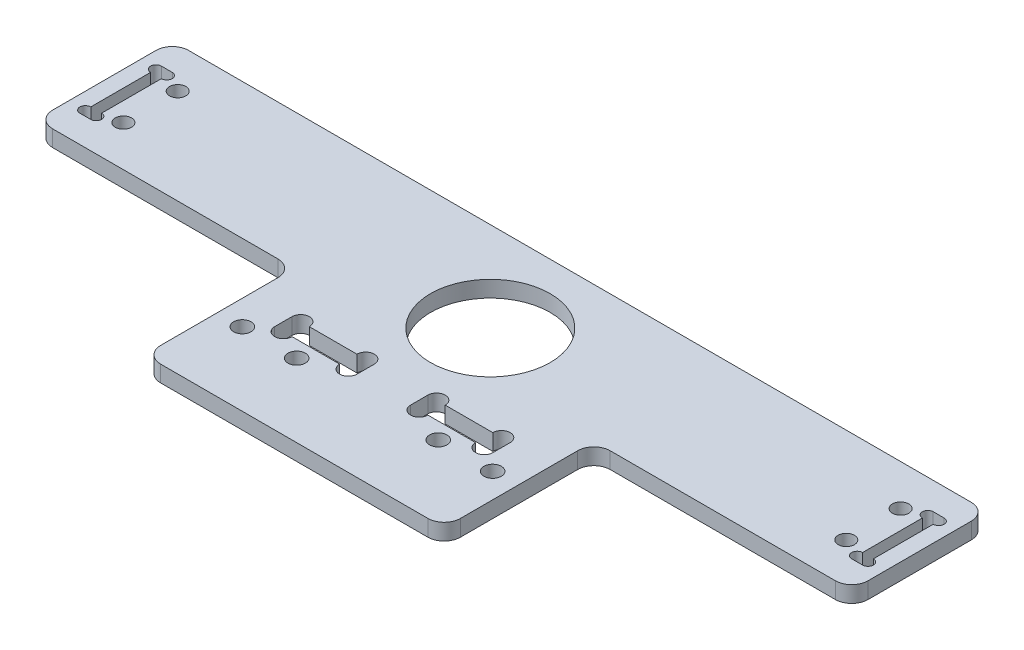
SolidWorks part; units mm, degrees
material "Thornel Mat VMA"
ref_plane "前视基准面" through (0, 0, 0) normal (0, 0, 1) x (1, 0, 0)
ref_plane "上视基准面" through (0, 0, 0) normal (0, 1, 0) x (1, 0, 0)
ref_plane "右视基准面" through (0, 0, 0) normal (1, 0, 0) x (0, 0, -1)
other "Configuration Table"
sketch "草图1" plane through (0, 0, 0) normal (0, 1, 0) x (1, 0, 0)
  line L0 (30.075, -69.59) -> (30.075, -66.41)
  line L1 (22.5, -69.59) -> (22.5, -66.41) construction
  line L7 (30.075, -68) -> (14.925, -68) construction
  line L8 (26.875, -69.59) -> (18.125, -69.59)
  line L9 (26.875, -66.41) -> (18.125, -66.41)
  line L14 (43.125, 69.59) -> (51.875, 69.59)
  line L15 (39.925, 69.59) -> (39.925, 66.41)
  line L16 (43.125, 66.41) -> (51.875, 66.41)
  line L17 (55.075, 69.59) -> (55.075, 66.41)
  line L18 (55.075, -69.59) -> (55.075, -66.41)
  line L19 (43.125, -66.41) -> (51.875, -66.41)
  line L20 (39.925, -69.59) -> (39.925, -66.41)
  line L21 (43.125, -69.59) -> (51.875, -69.59)
  line L22 (47.5, 69.59) -> (47.5, 66.41) construction
  line L23 (39.925, 68) -> (55.075, 68) construction
  line L24 (39.925, -68) -> (55.075, -68) construction
  line L25 (47.5, -69.59) -> (47.5, -66.41) construction
  line L27 (14.925, -69.59) -> (14.925, -66.41)
  line L29 (-1, -77.5) -> (-40, -77.5)
  line L30 (30.075, 68) -> (14.925, 68) construction
  line L31 (22.5, 69.59) -> (22.5, 66.41) construction
  line L33 (-1, 77.5) -> (-40, 77.5)
  line L54 (71, 77.5) -> (110, 77.5)
  line L56 (35, 153.4687) -> (35, -164.7089) construction
  line L58 (71, -77.5) -> (110, -77.5)
  line L64 (110, 235.15) -> (110, 77.5)
  line L67 (14.925, 69.59) -> (14.925, 66.41)
  line L68 (26.875, 66.41) -> (18.125, 66.41)
  line L69 (26.875, 69.59) -> (18.125, 69.59)
  line L70 (30.075, 69.59) -> (30.075, 66.41)
  line L72 (-40, 235.15) -> (110, 235.15)
  line L74 (-40, -235.15) -> (110, -235.15)
  line L77 (71, 77.5) -> (71, 47.9372)
  line L78 (-1, 77.5) -> (-1, 47.9372)
  line L84 (-40, 235.15) -> (-40, 77.5)
  line L85 (-1, 47.9372) -> (-43.8991, 47.9372)
  line L86 (-43.8991, 47.9372) -> (-43.8991, -47.9372)
  line L90 (113.8991, 47.9372) -> (113.8991, -47.9372)
  line L91 (71, 47.9372) -> (113.8991, 47.9372)
  line L93 (71, -47.9372) -> (113.8991, -47.9372)
  line L94 (-1, -47.9372) -> (-43.8991, -47.9372)
  line L95 (110, -77.5) -> (110, -235.15)
  line L96 (-1, -47.9372) -> (-1, -77.5)
  line L97 (71, -47.9372) -> (71, -77.5)
  line L98 (-40, -77.5) -> (-40, -235.15)
  arc A8 (39.925, 69.59) -> (43.125, 69.59) centre (41.525, 69.59) cw
  arc A9 (55.075, 69.59) -> (51.875, 69.59) centre (53.475, 69.59) ccw
  arc A10 (55.075, 66.41) -> (51.875, 66.41) centre (53.475, 66.41) cw
  arc A11 (39.925, 66.41) -> (43.125, 66.41) centre (41.525, 66.41) ccw
  arc A12 (39.925, -66.41) -> (43.125, -66.41) centre (41.525, -66.41) cw
  arc A13 (55.075, -66.41) -> (51.875, -66.41) centre (53.475, -66.41) ccw
  arc A14 (55.075, -69.59) -> (51.875, -69.59) centre (53.475, -69.59) cw
  arc A15 (39.925, -69.59) -> (43.125, -69.59) centre (41.525, -69.59) ccw
  circle A50 centre (48.025, -63.59) radius 1.6
  circle A51 centre (58.025, -63.59) radius 1.6
  circle A52 centre (58.025, 63.41) radius 1.6
  circle A53 centre (48.025, 63.41) radius 1.6
  arc A54 (30.075, -69.59) -> (26.875, -69.59) centre (28.475, -69.59) cw
  arc A55 (30.075, -66.41) -> (26.875, -66.41) centre (28.475, -66.41) ccw
  circle A56 centre (11.975, -63.59) radius 1.6
  circle A57 centre (21.975, -63.59) radius 1.6
  arc A58 (14.925, -69.59) -> (18.125, -69.59) centre (16.525, -69.59) ccw
  arc A59 (14.925, -66.41) -> (18.125, -66.41) centre (16.525, -66.41) cw
  circle A60 centre (21.975, 63.41) radius 1.6
  circle A61 centre (11.975, 63.41) radius 1.6
  arc A62 (30.075, 66.41) -> (26.875, 66.41) centre (28.475, 66.41) cw
  arc A63 (14.925, 66.41) -> (18.125, 66.41) centre (16.525, 66.41) ccw
  arc A64 (14.925, 69.59) -> (18.125, 69.59) centre (16.525, 69.59) cw
  arc A65 (30.075, 69.59) -> (26.875, 69.59) centre (28.475, 69.59) ccw
  point P28 (35, -97.5)
  point P79 (35, 97.5)
  point P141 (64, 0)
  point P146 (-64, 0)
  dimension "D12" = 4.925
extrude "凸台-拉伸1" add sketch "草图1" along normal blind 3
sketch "草图5" plane through (0, 0, 0) normal (0, -1, 0) x (1, 0, 0)
  line L0 (71, 77.5) -> (62.5724, 77.5)
  line L1 (62.5724, 77.5) -> (62.5724, 47.9372)
  line L2 (62.5724, 47.9372) -> (71, 47.9372)
  line L3 (71, 47.9372) -> (71, 77.5)
  line L4 (35, 235.15) -> (35, -235.15) construction
  line L5 (-40, 235.15) -> (110, 235.15) construction
  line L6 (110, -235.15) -> (-40, -235.15) construction
  line L7 (113.8991, 0) -> (-40.3263, 0) construction
  line L8 (113.8991, 47.9372) -> (113.8991, -47.9372) construction
  line L9 (7.4276, 47.9372) -> (-1, 47.9372)
  line L10 (7.4276, 77.5) -> (7.4276, 47.9372)
  line L11 (-1, 77.5) -> (7.4276, 77.5)
  line L12 (-1, 47.9372) -> (-1, 77.5)
  line L13 (7.4276, -77.5) -> (7.4276, -47.9372)
  line L14 (-1, -77.5) -> (7.4276, -77.5)
  line L15 (-1, -47.9372) -> (-1, -77.5)
  line L16 (7.4276, -47.9372) -> (-1, -47.9372)
  line L17 (62.5724, -47.9372) -> (71, -47.9372)
  line L18 (62.5724, -77.5) -> (62.5724, -47.9372)
  line L19 (71, -77.5) -> (62.5724, -77.5)
  line L20 (71, -47.9372) -> (71, -77.5)
  line L22 (64.9124, 72.165) -> (64.9124, 53.165) construction
  dimension "D1" = 2.34
extrude "切除-拉伸4" cut sketch "草图5" against normal blind 10
sketch "草图7" plane through (0, 0, 0) normal (0, -1, 0) x (-1, 0, 0)
  line L0 (-109.7412, -0.165) -> (39.4412, -0.165) construction
  line L1 (-109.7412, 46.835) -> (-109.7412, -47.165) construction
  line L2 (39.4412, -47.165) -> (39.4412, 46.835) construction
  line L3 (-113.8991, 0) -> (-113.8991, -47.9372)
  line L4 (-113.8991, -47.9372) -> (-113.8991, 47.9372) construction
  line L5 (-113.8991, -47.9372) -> (-62.5724, -47.9372)
  line L6 (-62.5724, -47.9372) -> (-62.5724, -50.2772)
  line L7 (-62.5724, -77.5) -> (-62.5724, -47.9372) construction
  line L8 (-62.5724, -50.2772) -> (-7.4276, -50.2772)
  line L9 (-7.4276, -47.9372) -> (-7.4276, -77.5) construction
  line L10 (-7.4276, -50.2772) -> (-7.4276, -47.9372)
  line L11 (-7.4276, -47.9372) -> (43.8991, -47.9372)
  line L12 (43.8991, -47.9372) -> (43.8991, 0)
  line L13 (43.8991, 47.9372) -> (43.8991, -47.9372) construction
  line L14 (43.8991, 47.6072) -> (43.8991, -0.33)
  line L15 (-7.4276, 47.6072) -> (43.8991, 47.6072)
  line L16 (-7.4276, 49.9472) -> (-7.4276, 47.6072)
  line L17 (-62.5724, 49.9472) -> (-7.4276, 49.9472)
  line L18 (-62.5724, 47.6072) -> (-62.5724, 49.9472)
  line L19 (-113.8991, 47.6072) -> (-62.5724, 47.6072)
  line L20 (-113.8991, -0.33) -> (-113.8991, 47.6072)
  dimension "D1" = 2.34
extrude "切除-拉伸-薄壁1" cut sketch "草图7" against normal blind 100 thin
sketch "草图8" plane through (0, 0, 0) normal (0, -1, 0) x (-1, 0, 0)
  line L0 (78.2129, 60.3854) -> (0, 54.3266)
  line L1 (0, 54.3266) -> (-4.4819, 51.6726)
  line L2 (-4.4819, 51.6726) -> (-7.9389, 48.7614)
  line L3 (-7.9389, 48.7614) -> (-49.3319, 46.578)
  line L4 (-49.3319, 46.578) -> (-63.5238, 48.7614)
  line L5 (-63.5238, 48.7614) -> (-79.0802, 55.8574)
  line L6 (-79.0802, 55.8574) -> (-126.5637, 60.3854)
  line L7 (-126.5637, 60.3854) -> (-136.5618, 25.02)
  line L8 (-136.5618, 25.02) -> (-185.5093, -177.4679)
  line L9 (-185.5093, -177.4679) -> (-114.7988, -331.7415)
  line L10 (-114.7988, -331.7415) -> (230.8962, -266.4277)
  line L11 (230.8962, -266.4277) -> (230.8962, -108.9334)
  line L12 (230.8962, -108.9334) -> (223.6813, -70.7462)
  line L13 (223.6813, -70.7462) -> (78.2129, 60.3854)
extrude "切除-拉伸5" cut sketch "草图8" against normal blind 100
sketch "草图9" plane through (0, 0, 0) normal (0, -1, 0) x (1, 0, 0)
  line L0 (-40, -102.5) -> (110, -102.5)
  line L1 (-40, -235.15) -> (-40, -77.5) construction
  line L2 (110, -77.5) -> (110, -235.15) construction
  line L3 (110, -102.5) -> (124.2117, -119.6913)
  line L4 (124.2117, -119.6913) -> (154.9872, -211.5735)
  line L5 (154.9872, -211.5735) -> (124.2117, -286.8618)
  line L6 (124.2117, -286.8618) -> (-63.6735, -270.7015)
  line L7 (-63.6735, -270.7015) -> (-75.5561, -182.7703)
  line L8 (-75.5561, -182.7703) -> (-74.082, -165.6324)
  line L9 (-74.082, -165.6324) -> (-40, -102.5)
  line L10 (-40, -77.5) -> (7.4276, -77.5) construction
  dimension "D1" = 25
extrude "切除-拉伸6" cut sketch "草图9" against normal blind 100
fillet "圆角3" radius 3 8 edges at (-40, 1.5, -102.5) (-40, 1.5, -77.5) (7.4276, 1.5, -77.5) (7.4276, 1.5, -49.9472) (62.5724, 1.5, -49.9472) (62.5724, 1.5, -77.5) (110, 1.5, -77.5) (110, 1.5, -102.5)
sketch "草图10" plane through (0, 0, 0) normal (0, -1, 0) x (1, 0, 0)
  line L0 (-40, -90) -> (116.9291, -90) construction
  line L1 (-40, -99.5) -> (-40, -80.5) construction
  line L2 (35, -49.9472) -> (35, -107.9395) construction
  line L3 (-37, -82.5) -> (-35, -82.5)
  line L4 (-37, -82.5) -> (-37, -97.5)
  line L5 (-37, -97.5) -> (-35, -97.5)
  line L6 (-35, -82.5) -> (-35, -97.5)
  line L7 (-37, -82.5) -> (-35, -97.5) construction
  line L8 (-37, -97.5) -> (-35, -82.5) construction
  line L9 (59.5724, -49.9472) -> (10.4276, -49.9472) construction
  line L10 (-37, -83.5) -> (-35, -83.5) construction
  line L11 (-37, -82.5) -> (-35, -82.5)
  line L12 (-37, -84.5) -> (-35, -84.5)
  line L13 (-37, -96.5) -> (-35, -96.5) construction
  line L14 (-37, -95.5) -> (-35, -95.5)
  line L15 (-37, -97.5) -> (-35, -97.5)
  line L16 (107, -97.5) -> (105, -82.5) construction
  line L17 (107, -82.5) -> (105, -97.5) construction
  line L18 (105, -82.5) -> (105, -97.5)
  line L19 (107, -97.5) -> (105, -97.5)
  line L20 (107, -82.5) -> (107, -97.5)
  line L21 (107, -82.5) -> (105, -82.5)
  line L22 (107, -96.5) -> (105, -96.5) construction
  line L23 (107, -95.5) -> (105, -95.5)
  line L24 (107, -97.5) -> (105, -97.5)
  line L25 (107, -83.5) -> (105, -83.5) construction
  line L26 (107, -82.5) -> (105, -82.5)
  line L27 (107, -84.5) -> (105, -84.5)
  circle A0 centre (-31.5, -85) radius 1.5
  circle A1 centre (-31.5, -95) radius 1.5
  arc A2 (-37, -82.5) -> (-37, -84.5) centre (-37, -83.5) ccw
  arc A3 (-35, -84.5) -> (-35, -82.5) centre (-35, -83.5) ccw
  arc A4 (-37, -95.5) -> (-37, -97.5) centre (-37, -96.5) ccw
  arc A5 (-35, -97.5) -> (-35, -95.5) centre (-35, -96.5) ccw
  circle A6 centre (101.5, -95) radius 1.5
  circle A7 centre (101.5, -85) radius 1.5
  arc A8 (107, -95.5) -> (107, -97.5) centre (107, -96.5) cw
  arc A9 (105, -97.5) -> (105, -95.5) centre (105, -96.5) cw
  arc A10 (107, -82.5) -> (107, -84.5) centre (107, -83.5) cw
  arc A11 (105, -84.5) -> (105, -82.5) centre (105, -83.5) cw
  point P4 (-36, -90)
  point P19 (-36, -83.5)
  point P24 (-36, -96.5)
  point P41 (106, -96.5)
  point P46 (106, -83.5)
  point P49 (106, -90)
  dimension "D4" = 3
  dimension "D7" = 1
  dimension "D8" = 1
  dimension "D1" = 2
  dimension "D2" = 15
  dimension "D3" = 3
  dimension "D5" = 5
  dimension "D6" = 3.5
extrude "切除-拉伸7" cut sketch "草图10" against normal blind 10 contours L6 A3 | L4 A2 | L4 L12 L6 L3 | L4 L14 L6 L12 | L14 L4 L5 L6 | L4 A4 | L6 A5 | A1 | A0 | A8 L20 | L20 L23 L18 L19 | A9 L18 | L20 L27 L18 L23 | A10 L20 | L27 L20 L21 L18 | A11 L18 | A7 | A6
sketch "草图11" plane through (0, 0, 0) normal (0, -1, 0) x (1, 0, 0)
  circle A0 centre (35, -86.0155) radius 11
  dimension "D1" = 22
extrude "切除-拉伸8" cut sketch "草图11" against normal blind 10
